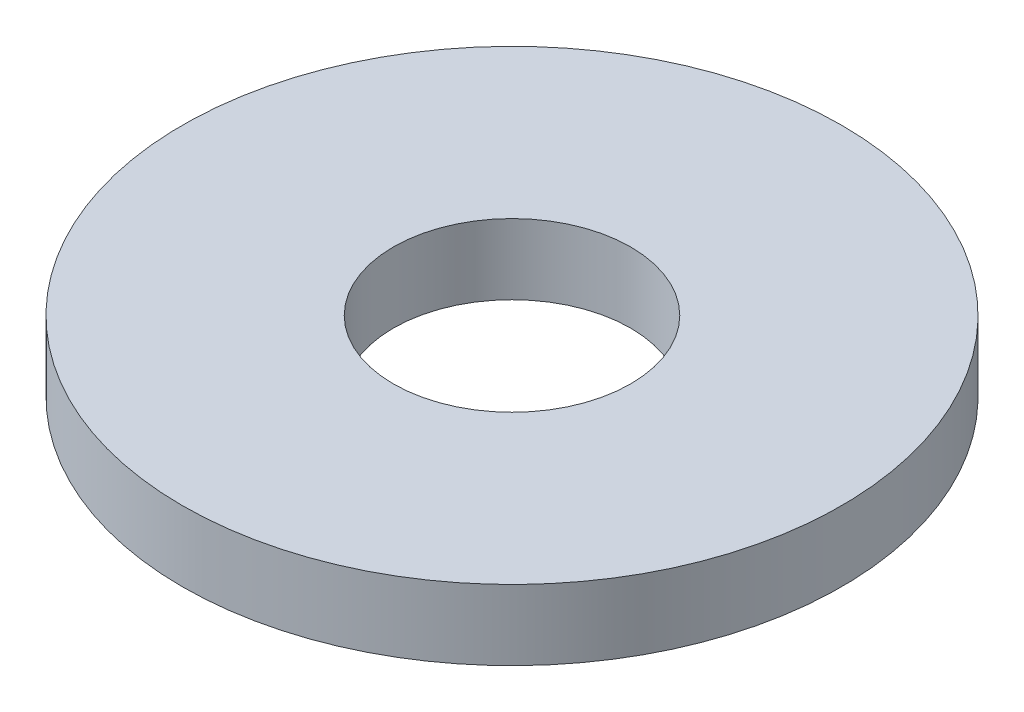
SolidWorks part; units mm, degrees
ref_plane "Front Plane" through (0, 0, 0) normal (0, 0, 1) x (1, 0, 0)
ref_plane "Top Plane" through (0, 0, 0) normal (0, 1, 0) x (1, 0, 0)
ref_plane "Right Plane" through (0, 0, 0) normal (1, 0, 0) x (0, 0, -1)
sketch "Sketch1" plane through (0, 0, 0) normal (0, 0, 1) x (1, 0, 0)
  line L0 (0, 0) -> (0, 0.8) construction
  line L1 (-1.35, 0) -> (-3.75, 0)
  line L3 (-1.35, 0.8) -> (-3.75, 0.8)
  line L4 (-3.75, 0) -> (-3.75, 0.8)
  line L5 (-1.35, 0.8) -> (-1.35, 0)
  line L8 (-1.25, 0.8) -> (1.25, 0.8) construction
revolve "Revolve1" add sketch "Sketch1" angle 360 about L0
equation "\"D2@Sketch1\"=3*\"Screw Size@Sketch1\""
equation "\"D3@Sketch1\"=0.2+\"Screw Size@Sketch1\""
